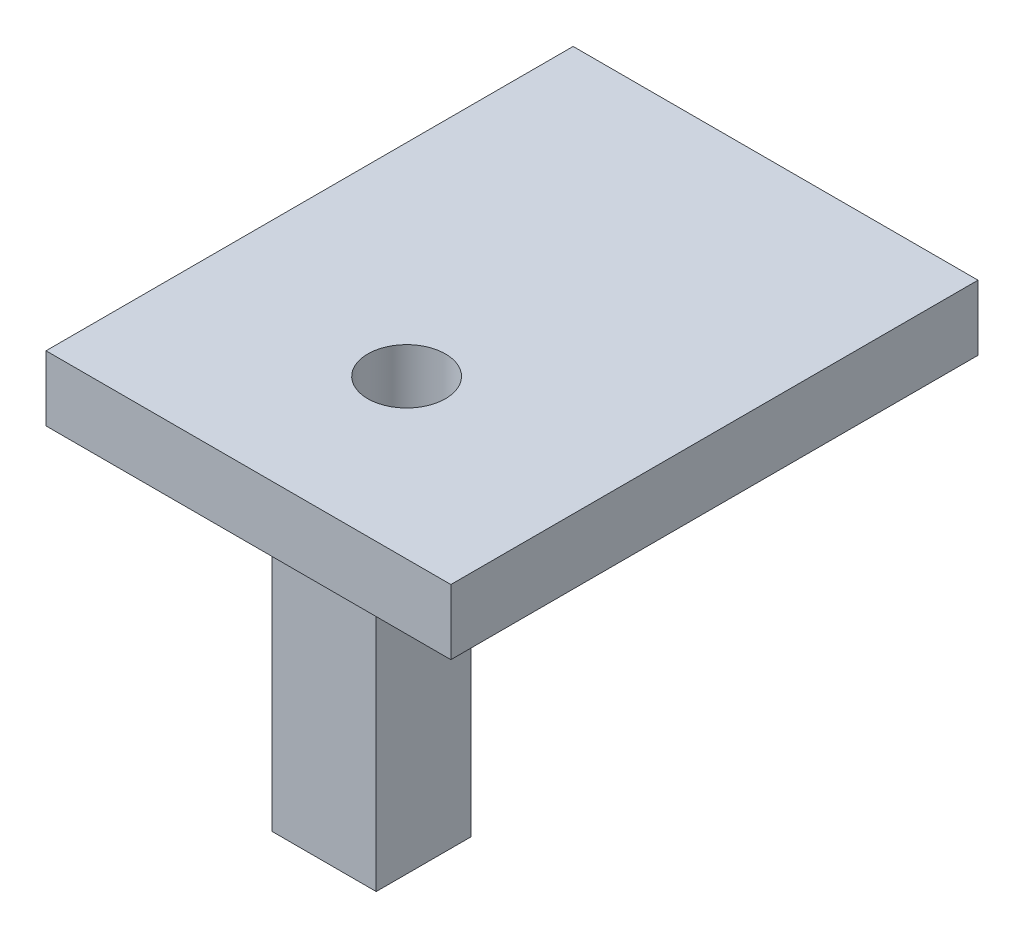
SolidWorks part; units mm, degrees
ref_plane "Front Plane" through (0, 0, 0) normal (0, 0, 1) x (1, 0, 0)
ref_plane "Top Plane" through (0, 0, 0) normal (0, 1, 0) x (1, 0, 0)
ref_plane "Right Plane" through (0, 0, 0) normal (1, 0, 0) x (0, 0, -1)
sketch "Sketch1" plane through (0, 0, 0) normal (0, 1, 0) x (1, 0, 0)
  line L1 (-31.1, 40.4921) -> (31.1, 40.4921)
  line L2 (-31.1, 40.4921) -> (-31.1, -40.4921)
  line L3 (-31.1, -40.4921) -> (31.1, -40.4921)
  line L4 (31.1, 40.4921) -> (31.1, -40.4921)
  line L5 (-31.1, 40.4921) -> (31.1, -40.4921) construction
  line L6 (-31.1, -40.4921) -> (31.1, 40.4921) construction
  point P0 (0, 0)
  dimension "D1" = 62.2
  dimension "D2" = 80.9841
extrude "Boss-Extrude1" add sketch "Sketch1" along normal blind 10
sketch "Sketch2" plane through (0, 10, 0) normal (0, 1, 0) x (1, 0, 0)
  line L0 (-31.1, -40.4921) -> (31.1, -40.4921) construction
  circle A0 centre (0, -16.1921) radius 5.969
  dimension "D1" = 24.3
extrude "Cut-Extrude1" cut sketch "Sketch2" against normal blind 10
sketch "Sketch3" plane through (0, 0, 0) normal (0, -1, 0) x (1, 0, 0)
  line L0 (31.1, -40.4921) -> (-31.1, -40.4921) construction
  line L1 (-15.1, -8.7921) -> (-31.1, -8.7921)
  line L2 (-15.1, -8.7921) -> (-15.1, 5.7606)
  line L3 (-15.1, 5.7606) -> (-31.1, 5.7606)
  line L4 (-31.1, -8.7921) -> (-31.1, 5.7606)
  line L5 (-31.1, -40.4921) -> (-31.1, 40.4921) construction
  dimension "D1" = 16
  dimension "D2" = 31.7
  dimension "D3" = 14.5526
  dimension "D4" = 0
extrude "Boss-Extrude2" add sketch "Sketch3" along normal blind 71.32
